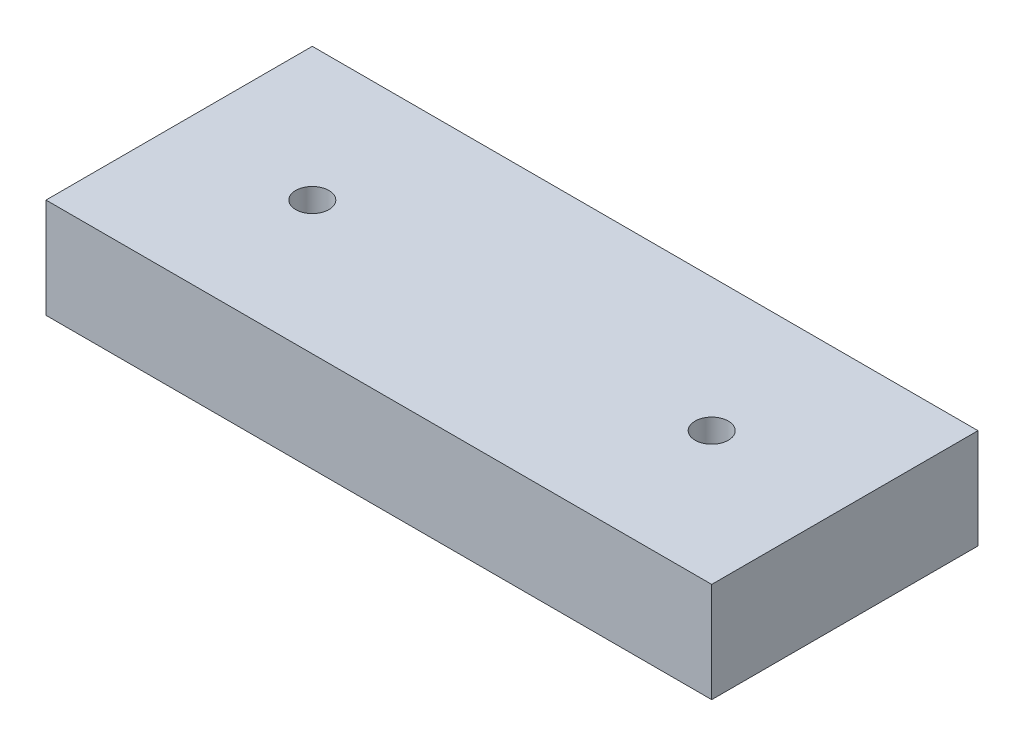
SolidWorks part; units mm, degrees
ref_plane "Ebene vorne" through (0, 0, 0) normal (0, 0, 1) x (1, 0, 0)
ref_plane "Ebene oben" through (0, 0, 0) normal (0, 1, 0) x (1, 0, 0)
ref_plane "Ebene rechts" through (0, 0, 0) normal (1, 0, 0) x (0, 0, -1)
sketch "Sketch1" plane through (0, 0, 0) normal (0, 1, 0) x (1, 0, 0)
  line L0 (-13.6, 5.1796) -> (-20, 5.1796) construction
  line L1 (0, 8) -> (-20, 8)
  line L2 (0, 8) -> (0, 0)
  line L3 (0, 0) -> (-20, 0)
  line L4 (-20, 8) -> (-20, 0)
  line L5 (-13.6, 9.5537) -> (-6.4, 9.5537) construction
  line L6 (-13.6, 9.5537) -> (-13.6, -1.1463) construction
  line L7 (-13.6, -1.1463) -> (-6.4, -1.1463) construction
  line L8 (-6.4, 9.5537) -> (-6.4, -1.1463) construction
  line L9 (-6.4, 5.1796) -> (0, 5.1796) construction
  dimension "D1" = 7.2
  dimension "D2" = 10.7
  dimension "D3" = 20
extrude "Boss-Extrude1" add sketch "Sketch1" along normal blind 3
sketch "Sketch4" plane through (0, 3, 0) normal (0, 1, 0) x (1, 0, 0)
  line L0 (-20, 8) -> (-20, 0) construction
  line L1 (0, 8) -> (0, 0) construction
  circle A0 centre (-16, 4) radius 0.5
  circle A1 centre (-4, 4) radius 0.5
  dimension "D1" = 4
  dimension "D2" = 4
extrude "Cut-Extrude1" cut sketch "Sketch4" against normal through all
